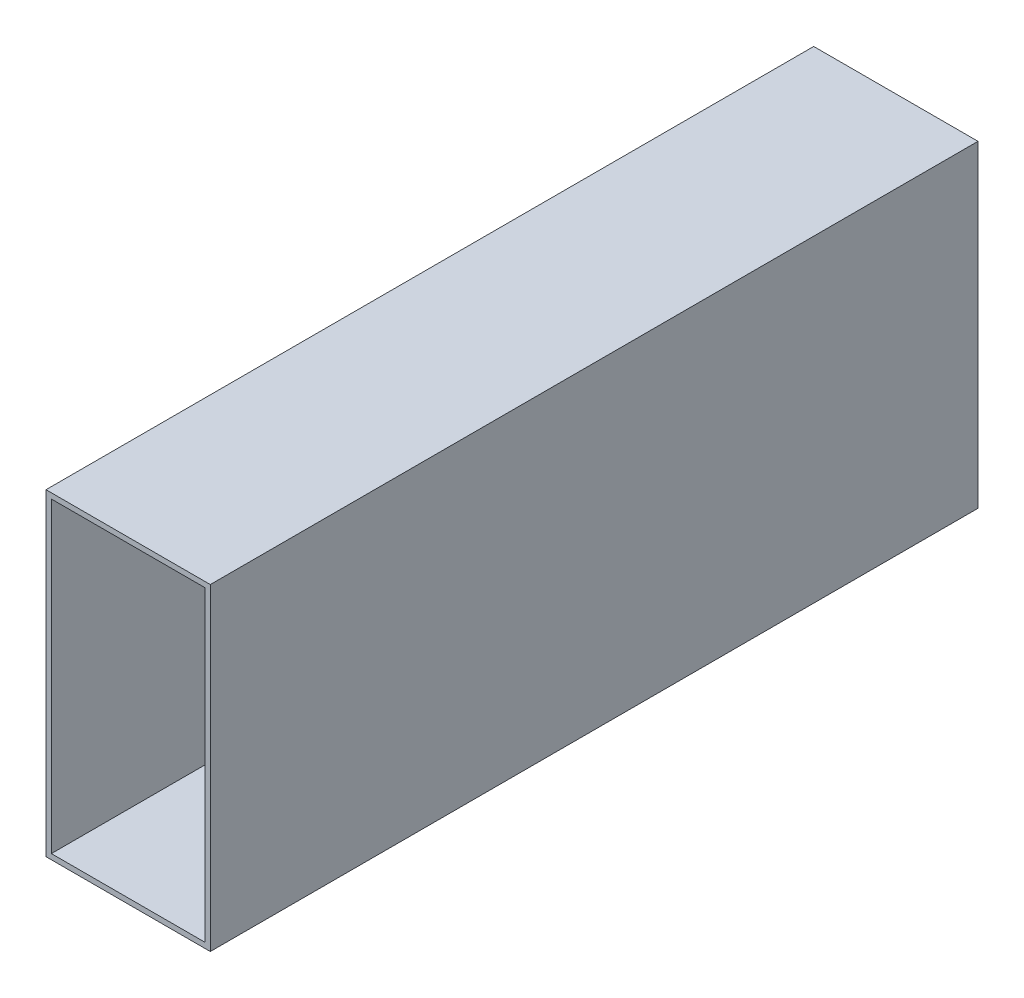
SolidWorks part; units mm, degrees
material "Thornel VCB-20 Carbon Cloth"
ref_plane "Front Plane" through (0, 0, 0) normal (0, 0, 1) x (1, 0, 0)
ref_plane "Top Plane" through (0, 0, 0) normal (0, 1, 0) x (1, 0, 0)
ref_plane "Right Plane" through (0, 0, 0) normal (1, 0, 0) x (0, 0, -1)
sketch "Sketch1" plane through (0, 0, 0) normal (0, 0, 1) x (1, 0, 0)
  line L1 (0, 0) -> (27.178, 0)
  line L2 (0, 0) -> (0, 52.578)
  line L3 (0, 52.578) -> (27.178, 52.578)
  line L4 (27.178, 0) -> (27.178, 52.578)
  dimension "D1" = 52.578
  dimension "D2" = 27.178
extrude "Boss-Extrude1" add sketch "Sketch1" along normal blind 127 contours L3 L4 L1 L2
shell "Shell1" thickness 0.889
